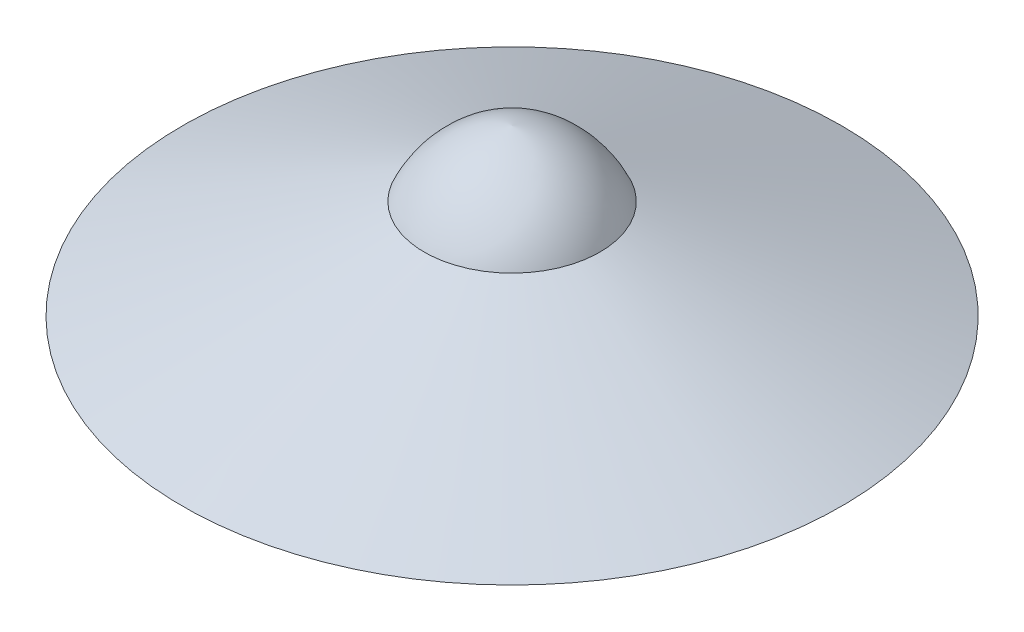
SolidWorks part; units mm, degrees
ref_plane "Спереди" through (0, 0, 0) normal (0, 0, 1) x (1, 0, 0)
ref_plane "Сверху" through (0, 0, 0) normal (0, 1, 0) x (1, 0, 0)
ref_plane "Справа" through (0, 0, 0) normal (1, 0, 0) x (0, 0, -1)
sketch "Эскиз1" plane through (0, 0, 0) normal (1, 0, 0) x (0, 0, -1)
  line L0 (0, 0) -> (6, 0)
  line L1 (6, 0) -> (1.5996, 1.806)
  line L2 (0, 0) -> (0, 3)
  arc A0 (1.5996, 1.806) -> (0, 3) centre (-0.2894, 0.9439) ccw
  dimension "D5" = 2.0764
  dimension "D1" = 3
  dimension "D2" = 6
  dimension "D3" = 4.4004
  dimension "D4" = 22.313
  dimension "D6" = 0
  dimension "D7" = 0
revolve "Повернуть1" add sketch "Эскиз1" angle 360 about L2
